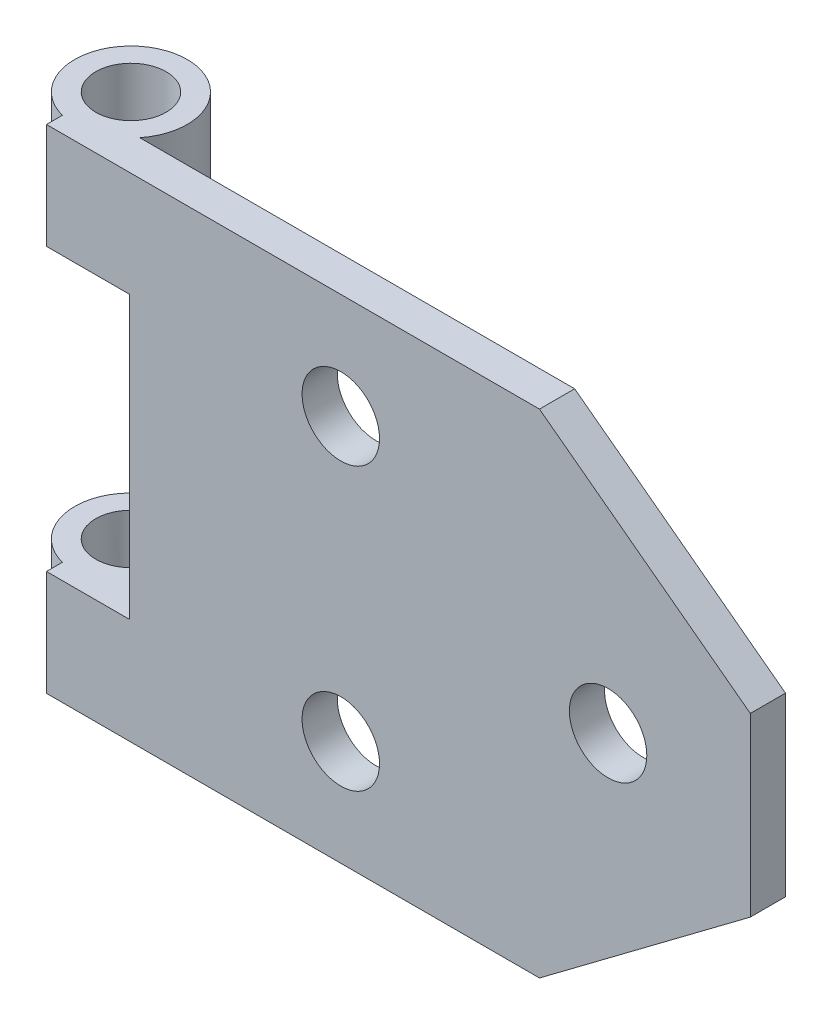
SolidWorks part; units mm, degrees
ref_plane "Front Plane" through (0, 0, 0) normal (0, 0, 1) x (1, 0, 0)
ref_plane "Top Plane" through (0, 0, 0) normal (0, 1, 0) x (1, 0, 0)
ref_plane "Right Plane" through (0, 0, 0) normal (1, 0, 0) x (0, 0, -1)
sketch "Sketch1" plane through (0, 0, 0) normal (0, 0, 1) x (1, 0, 0)
  line L0 (0, 0) -> (0, 15)
  line L1 (0, 15) -> (11.8238, 15)
  line L2 (11.8238, 15) -> (11.8238, 55)
  line L3 (11.8238, 55) -> (0, 55)
  line L4 (0, 55) -> (0, 70)
  line L5 (0, 70) -> (70.0436, 70)
  line L6 (70.0436, 70) -> (100, 47.5327)
  line L7 (100, 47.5327) -> (100, 22.4673)
  line L8 (100, 22.4673) -> (70.0436, 0)
  line L9 (70.0436, 0) -> (0, 0)
  circle A0 centre (41.815, 55) radius 5.5012
  circle A1 centre (41.815, 15) radius 5.5012
  circle A2 centre (79.79, 35) radius 5.5012
  dimension "D7" = 11.0024
  dimension "D1" = 100
  dimension "D2" = 70
  dimension "D3" = 11.8238
  dimension "D4" = 40
  dimension "D5" = 37.4455
  dimension "D6" = 25.0654
  dimension "D8" = 41.815
  dimension "D9" = 79.79
  dimension "D10" = 35
extrude "Boss-Extrude1" add sketch "Sketch1" along normal blind 5
sketch "Sketch2" plane through (0, 0, 0) normal (0, 1, 0) x (1, 0, 0)
  line L0 (70.0436, 0) -> (0, 0) construction
  line L1 (0, -5) -> (0, 0) construction
  circle A0 centre (2, 5) radius 5
  circle A1 centre (2, 5) radius 8
  dimension "D1" = 10
  dimension "D2" = 2
  dimension "D3" = 3
extrude "Boss-Extrude2" add sketch "Sketch2" along normal blind 70
sketch "Sketch3" plane through (0, 0, 0) normal (0, 0, 1) x (1, 0, 0)
  line L0 (-6, 55) -> (11.8238, 55)
  line L1 (-6, 70) -> (-6, 0) construction
  line L2 (11.8238, 55) -> (11.8238, 15)
  line L3 (11.8238, 15) -> (-6, 15)
  line L4 (-6, 15) -> (-6, 55)
extrude "Cut-Extrude1" cut sketch "Sketch3" against normal through all both and the other way through all
